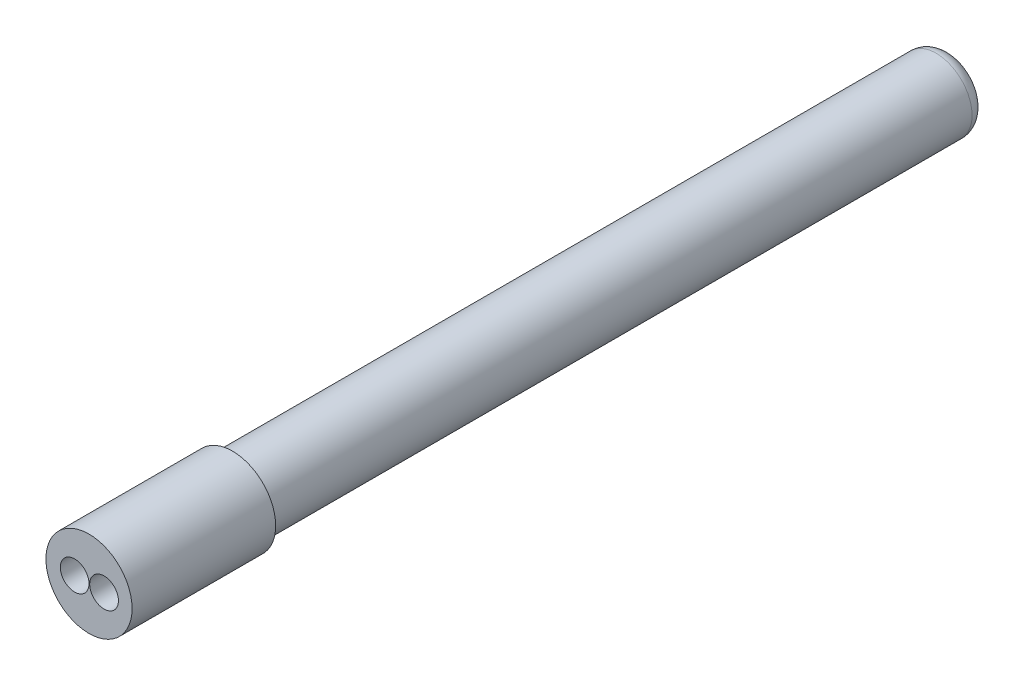
SolidWorks part; units mm, degrees
ref_plane "Front Plane" through (0, 0, 0) normal (0, 0, 1) x (1, 0, 0)
ref_plane "Top Plane" through (0, 0, 0) normal (0, 1, 0) x (1, 0, 0)
ref_plane "Right Plane" through (0, 0, 0) normal (1, 0, 0) x (0, 0, -1)
sketch "Sketch1" plane through (0, 0, 0) normal (0, 0, 1) x (1, 0, 0)
  circle A0 centre (0, 0) radius 5
  dimension "D1" = 10
extrude "Boss-Extrude1" add sketch "Sketch1" along normal blind 100
fillet "Fillet3" radius 2 1 edges at (5, 0, 0)
sketch "Sketch2" plane through (0, 0, 100) normal (0, 0, 1) x (1, 0, 0)
  circle A0 centre (0, 0) radius 6
  dimension "D1" = 12
extrude "Boss-Extrude2" add sketch "Sketch2" along normal blind 20
sketch "Sketch3" plane through (0, 0, 120) normal (0, 0, 1) x (1, 0, 0)
  circle A0 centre (-2, 0) radius 2
  circle A1 centre (2.1, 0) radius 2
  circle A2 centre (0, 0) radius 6 construction
  dimension "D1" = 2.1
  dimension "D2" = 4
  dimension "D3" = 4
extrude "Cut-Extrude2" cut sketch "Sketch3" against normal blind 20
